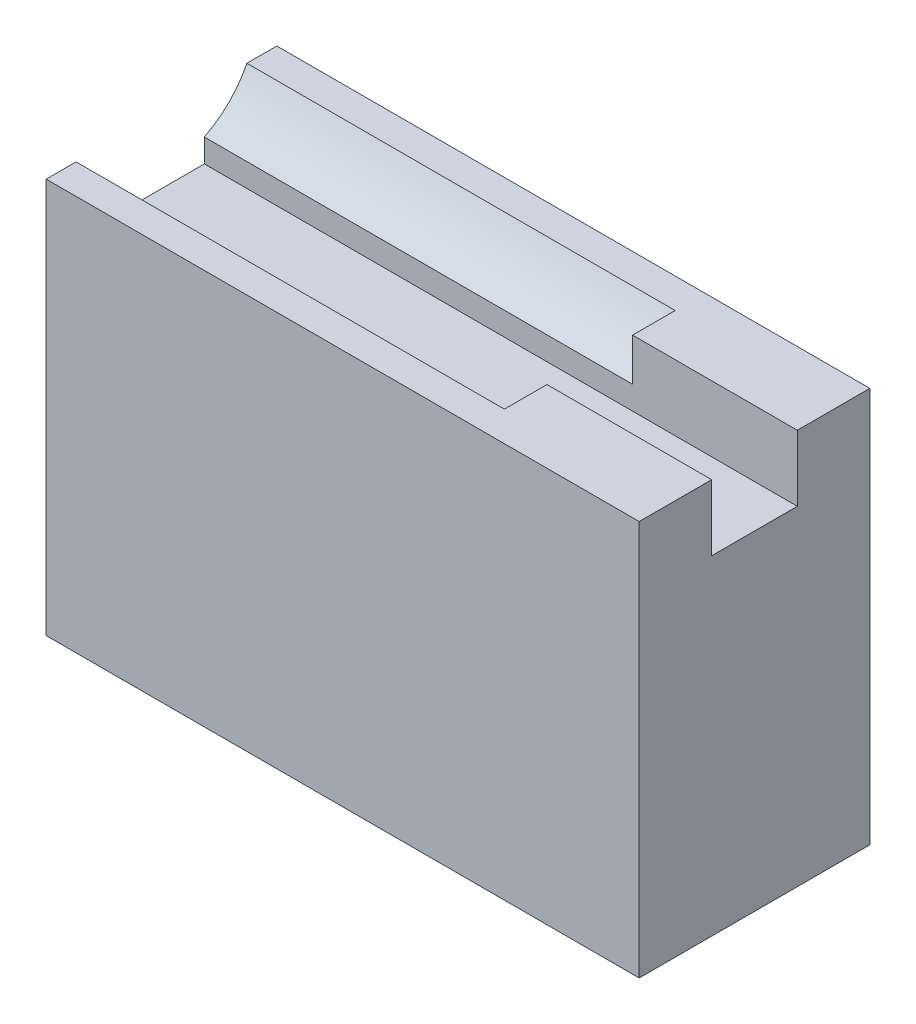
SolidWorks part; units mm, degrees
ref_plane "Front Plane" through (0, 0, 0) normal (0, 0, 1) x (1, 0, 0)
ref_plane "Top Plane" through (0, 0, 0) normal (0, 1, 0) x (1, 0, 0)
ref_plane "Right Plane" through (0, 0, 0) normal (1, 0, 0) x (0, 0, -1)
sketch "Sketch1" plane through (0, 0, 0) normal (0, 1, 0) x (1, 0, 0)
  line L1 (0, 0) -> (90, 0)
  line L2 (0, 0) -> (0, -35)
  line L3 (0, -35) -> (90, -35)
  line L4 (90, 0) -> (90, -35)
  dimension "D1" = 90
  dimension "D2" = 35
extrude "Boss-Extrude1" add sketch "Sketch1" along normal blind 60
sketch "Sketch2" plane through (0, 60, 0) normal (0, 1, 0) x (1, 0, 0)
  line L0 (90, -35) -> (90, 0) construction
  line L1 (90, -24) -> (65, -24)
  line L2 (90, -24) -> (90, -11)
  line L3 (90, -11) -> (65, -11)
  line L4 (65, -24) -> (65, -11)
  point P6 (90, -17.5)
  point P7 (90, -17.5)
  dimension "D1" = 13
  dimension "D2" = 0
  dimension "D3" = 25
extrude "Cut-Extrude1" cut sketch "Sketch2" against normal blind 8
sketch "Sketch3" plane through (65, 0, 0) normal (1, 0, 0) x (0, 0, -1)
  line L0 (-11, 52) -> (-24, 52) construction
  line L1 (0, 60) -> (-35, 60) construction
  circle A0 centre (-17.5, 66.5) radius 14.5
  point P6 (-17.5, 60)
  dimension "D1" = 29
  dimension "D2" = 14.5
  dimension "D3" = 0
extrude "Cut-Extrude2" cut sketch "Sketch3" against normal through all
sketch "Sketch4" plane through (0, 52, 0) normal (0, 1, 0) x (1, 0, 0)
  line L0 (0, -4.5385) -> (0, -30.4615) construction
  line L1 (90, -24) -> (-5.9391, -24)
  line L2 (90, -24) -> (90, -11)
  line L3 (90, -11) -> (-5.9391, -11)
  line L4 (-5.9391, -24) -> (-5.9391, -11)
  point P5 (90, -17.5)
  point P8 (0, -17.5)
  dimension "D1" = 0
extrude "Cut-Extrude8" cut sketch "Sketch4" against normal blind 2 and the other way through all
equation "\"D2@Sketch1\"=25+10"
equation "\"D2@Sketch3\"=\"D1@Sketch3\"/2"
